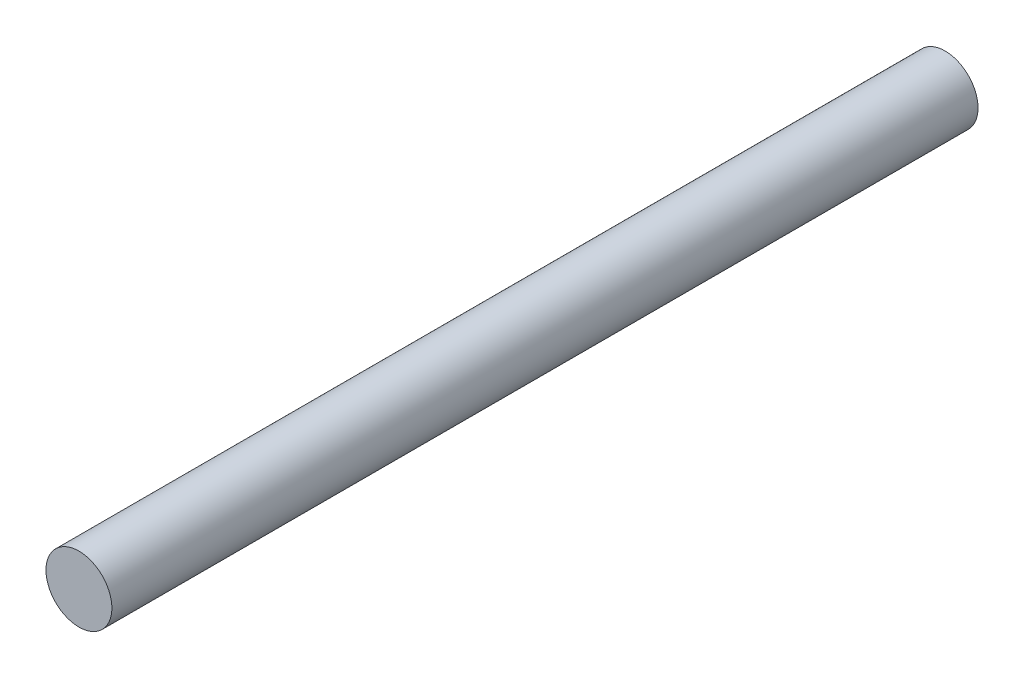
SolidWorks part; units mm, degrees
ref_plane "Front Plane" through (0, 0, 0) normal (0, 0, 1) x (1, 0, 0)
ref_plane "Top Plane" through (0, 0, 0) normal (0, 1, 0) x (1, 0, 0)
ref_plane "Right Plane" through (0, 0, 0) normal (1, 0, 0) x (0, 0, -1)
sketch "Sketch1" plane through (0, 0, 0) normal (0, 0, 1) x (1, 0, 0)
  line L1 (-3.175, 0) -> (3.175, 0) construction
  dimension "OD" = 6.35
sketch "Sketch2" plane through (0, 0, 0) normal (1, 0, 0) x (0, 0, -1)
  line L0 (41.75, 0) -> (-41.75, 0)
  point P4 (0, 0)
  dimension "Length" = 83.5
sketch "Sketch3" plane through (0, 0, 0) normal (0, 0, 1) x (1, 0, 0)
  circle A0 centre (0, 0) radius 3.175
extrude "Boss-Extrude1" add sketch "Sketch3" along normal up to vertex (41.75 mm away) and the other way up to vertex (41.75 mm away) up to point (0, 0, 41.75) other way up to point (0, 0, -41.75)
